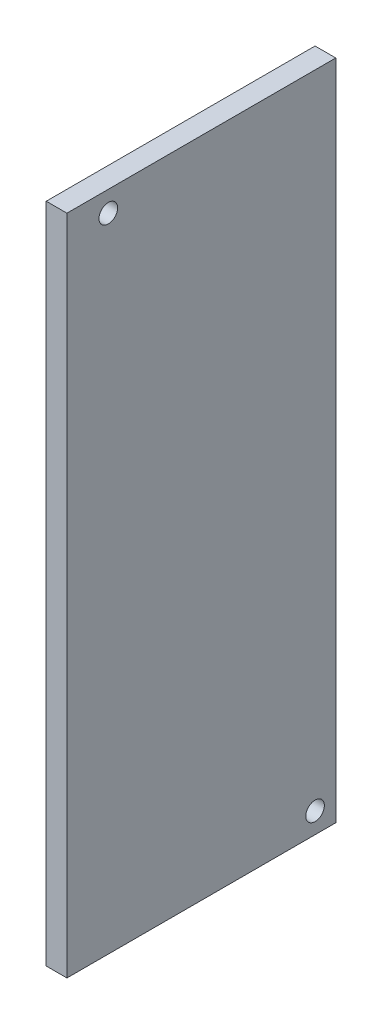
SolidWorks part; units mm, degrees
ref_plane "Front Plane" through (0, 0, 0) normal (1, 0, 0) x (0, 1, 0)
ref_plane "Top Plane" through (0, 0, 0) normal (0, 0, 1) x (0, 1, 0)
ref_plane "Right Plane" through (0, 0, 0) normal (0, 1, 0) x (-1, 0, 0)
sketch "Sketch1" plane through (0, 0, 0) normal (1, 0, 0) x (0, 1, 0)
  line L1 (80, 32.47) -> (-80, 32.47)
  line L2 (80, 32.47) -> (80, -32.47)
  line L3 (80, -32.47) -> (-80, -32.47)
  line L4 (-80, 32.47) -> (-80, -32.47)
  line L5 (80, 32.47) -> (-80, -32.47) construction
  line L6 (80, -32.47) -> (-80, 32.47) construction
  point P0 (0, 0)
  dimension "D1" = 160
  dimension "D2" = 64.94
extrude "Boss-Extrude1" add sketch "Sketch1" along normal blind 5
sketch "Sketch2" plane through (5, 0, 0) normal (1, 0, 0) x (0, 1, 0)
  line L0 (-80, 32.47) -> (-80, -32.47) construction
  line L1 (-80, -32.47) -> (80, -32.47) construction
  line L5 (80, 32.47) -> (-80, 32.47) construction
  line L6 (80, -32.47) -> (80, 32.47) construction
  circle A0 centre (-75, -27.47) radius 2.25
  circle A2 centre (75, 22.47) radius 2.25
  point P10 (75.8881, 33.7767)
  dimension "D1" = 4.5
  dimension "D2" = 5
  dimension "D3" = 5
  dimension "D4" = 10
  dimension "D5" = 5
extrude "Cut-Extrude1" cut sketch "Sketch2" against normal through all both and the other way through all
